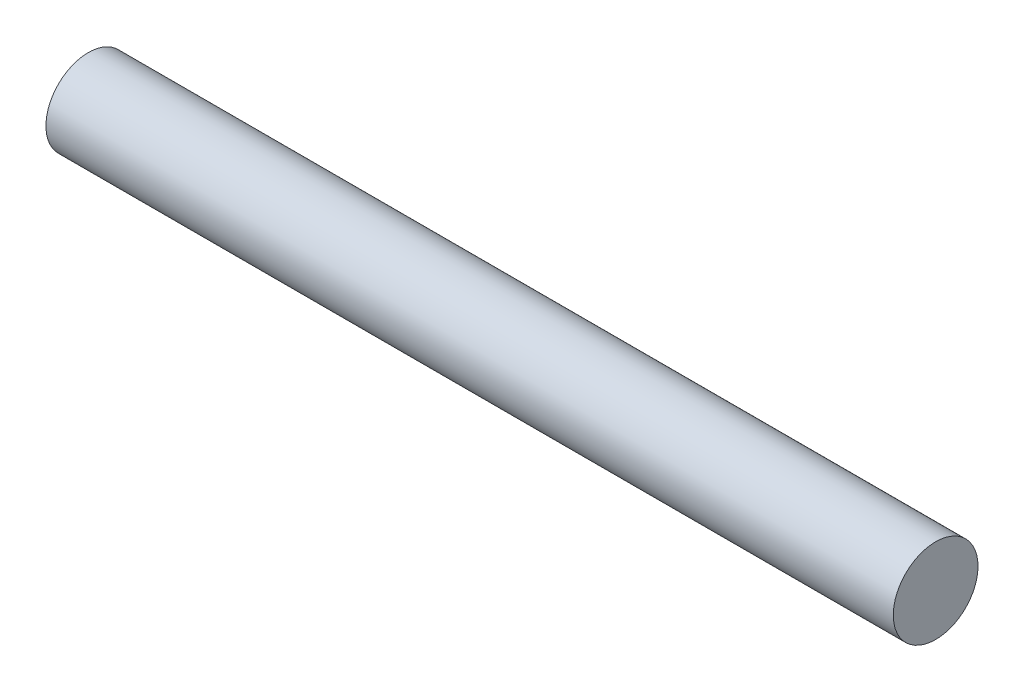
SolidWorks part; units mm, degrees
ref_plane "Front Plane" through (0, 0, 0) normal (0, 0, 1) x (1, 0, 0)
ref_plane "Top Plane" through (0, 0, 0) normal (0, 1, 0) x (1, 0, 0)
ref_plane "Right Plane" through (0, 0, 0) normal (1, 0, 0) x (0, 0, -1)
sketch "Sketch1" plane through (0, 0, 0) normal (1, 0, 0) x (0, 0, -1)
  circle A0 centre (0, 0) radius 10
  dimension "D1" = 20
extrude "Boss-Extrude1" add sketch "Sketch1" along normal blind 200
